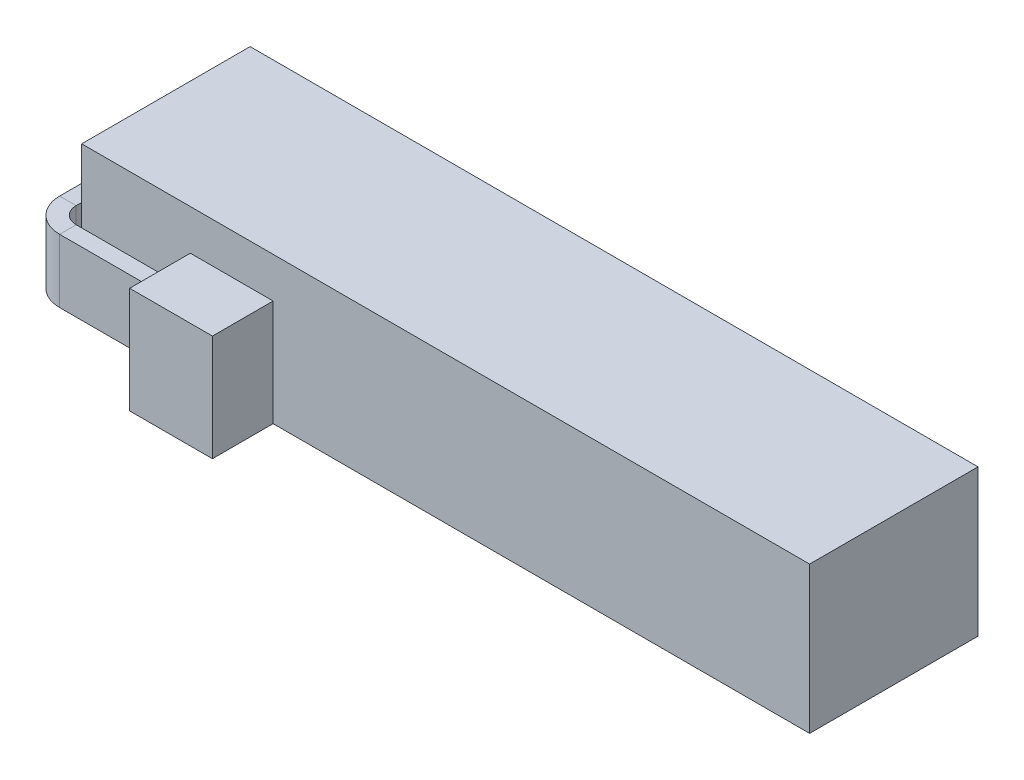
SolidWorks part; units mm, degrees
ref_plane "Front Plane" through (0, 0, 0) normal (0, 0, 1) x (1, 0, 0)
ref_plane "Top Plane" through (0, 0, 0) normal (0, 1, 0) x (1, 0, 0)
ref_plane "Right Plane" through (0, 0, 0) normal (1, 0, 0) x (0, 0, -1)
sketch "Sketch1" plane through (0, 0, 0) normal (1, 0, 0) x (0, 0, -1)
  line L1 (7.75, -6.75) -> (-7.75, -6.75)
  line L2 (7.75, -6.75) -> (7.75, 6.75)
  line L3 (7.75, 6.75) -> (-7.75, 6.75)
  line L4 (-7.75, -6.75) -> (-7.75, 6.75)
  line L5 (7.75, -6.75) -> (-7.75, 6.75) construction
  line L6 (7.75, 6.75) -> (-7.75, -6.75) construction
  point P0 (0, 0)
  point P5 (0, 0)
  dimension "D1" = 15.5
  dimension "D2" = 13.5
extrude "Boss-Extrude1" add sketch "Sketch1" along normal blind 67
sketch "Sketch2" plane through (0, 0, 7.75) normal (0, 0, 1) x (1, 0, 0)
  line L0 (67, -6.75) -> (0, -6.75) construction
  line L1 (10, -6.75) -> (17.62, -6.75)
  line L2 (10, -6.75) -> (10, 3.029)
  line L3 (10, 3.029) -> (17.62, 3.029)
  line L4 (17.62, -6.75) -> (17.62, 3.029)
  line L5 (0, 6.75) -> (0, -6.75) construction
  dimension "D1" = 7.62
  dimension "D2" = 9.779
  dimension "D3" = 10
extrude "Boss-Extrude2" add sketch "Sketch2" along normal blind 5.588
sketch "Sketch3" plane through (0, 0, 0) normal (0, 1, 0) x (1, 0, 0)
  line L0 (-0.762, 7.75) -> (-0.762, -7.242)
  line L1 (0.508, -8.512) -> (10, -8.512)
  line L2 (67, -7.75) -> (0, -7.75) construction
  line L3 (0, 7.75) -> (0, -7.75) construction
  line L4 (67, 7.75) -> (0, 7.75) construction
  line L5 (10, -13.338) -> (10, -7.75) construction
  arc A0 (-0.762, -7.242) -> (0.508, -8.512) centre (0.508, -7.242) ccw
  point P7 (0, 0)
  point P10 (0, 0)
  point P13 (0, 0)
  dimension "D3" = 1.27
  dimension "D1" = 0.762
  dimension "D2" = 0.762
sketch "Sketch4" plane through (10, 0, 0) normal (-1, 0, 0) x (0, 0, 1)
  line L1 (8.766, 1.0605) -> (10.29, 1.0605)
  line L2 (8.766, 1.0605) -> (8.766, -4.7815)
  line L3 (8.766, -4.7815) -> (10.29, -4.7815)
  line L4 (10.29, 1.0605) -> (10.29, -4.7815)
  line L5 (13.338, -1.8605) -> (7.75, -1.8605) construction
  line L6 (13.338, 3.029) -> (13.338, -6.75) construction
  line L7 (7.75, 3.029) -> (7.75, -6.75) construction
  dimension "D1" = 1.524
  dimension "D2" = 5.842
  dimension "D3" = 1.016
sweep "Sweep1" add profiles "Sketch4" path "Sketch3"
